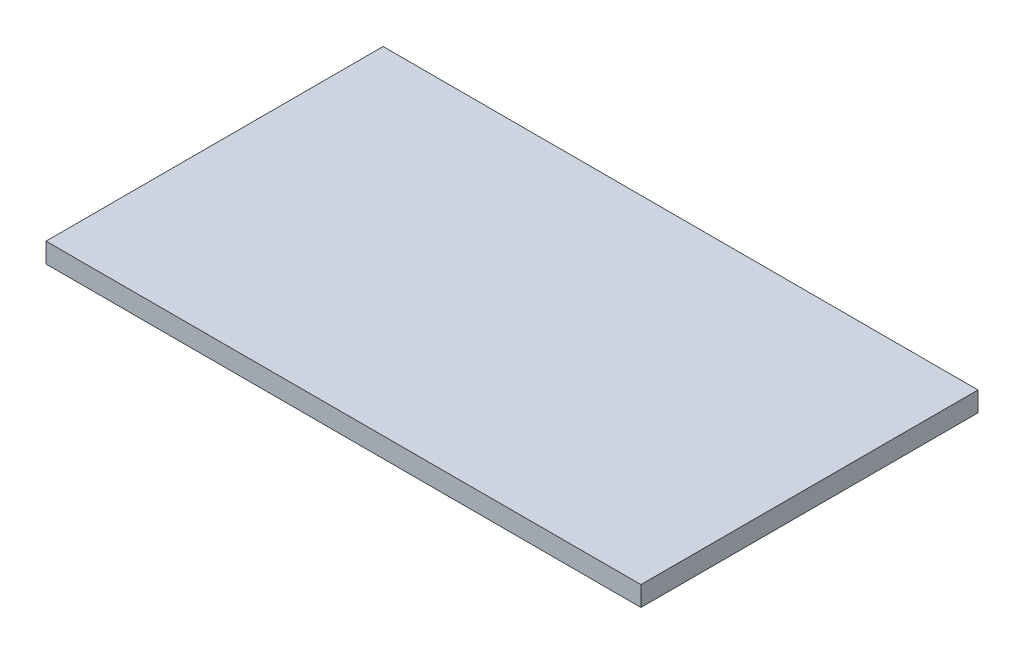
SolidWorks part; units mm, degrees
ref_plane "Front Plane" through (0, 0, 0) normal (0, 0, 1) x (1, 0, 0)
ref_plane "Top Plane" through (0, 0, 0) normal (0, 1, 0) x (1, 0, 0)
ref_plane "Right Plane" through (0, 0, 0) normal (1, 0, 0) x (0, 0, -1)
sketch "Sketch1" plane through (0, 0, 0) normal (0, 1, 0) x (1, 0, 0)
  line L1 (-150, -85) -> (150, -85)
  line L2 (-150, -85) -> (-150, 85)
  line L3 (-150, 85) -> (150, 85)
  line L4 (150, -85) -> (150, 85)
  line L5 (-150, -85) -> (150, 85) construction
  line L6 (-150, 85) -> (150, -85) construction
  point P0 (0, 0)
  dimension "D1" = 300
  dimension "D2" = 170
extrude "Boss-Extrude1" add sketch "Sketch1" along normal blind 10
